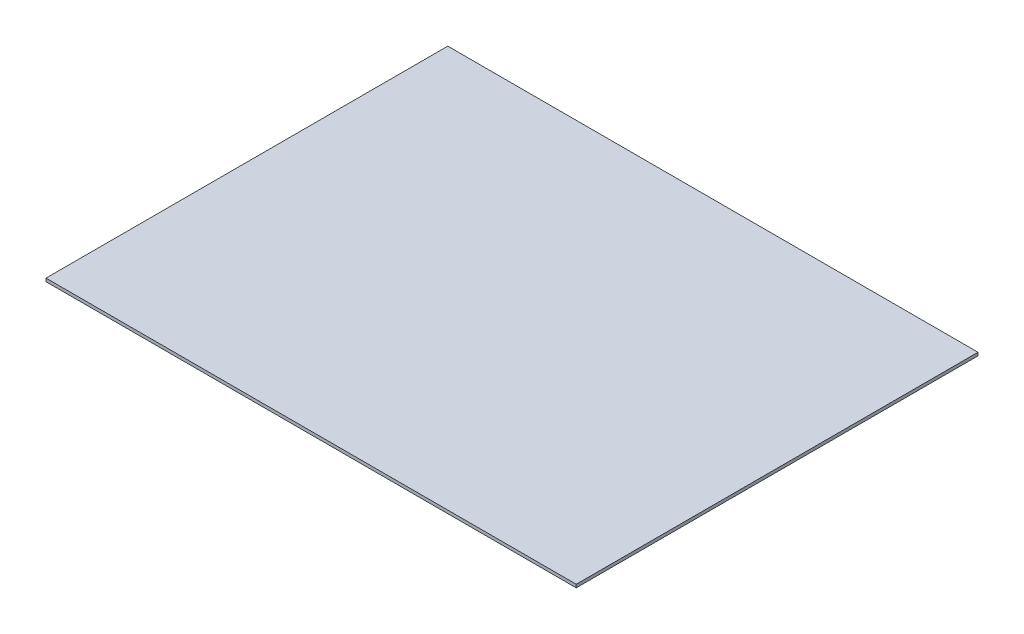
SolidWorks part; units mm, degrees
material "ABS"
ref_plane "Front Plane" through (0, 0, 0) normal (0, 0, 1) x (1, 0, 0)
ref_plane "Top Plane" through (0, 0, 0) normal (0, 1, 0) x (1, 0, 0)
ref_plane "Right Plane" through (0, 0, 0) normal (1, 0, 0) x (0, 0, -1)
sketch "Sketch1" plane through (0, 0, 0) normal (0, 1, 0) x (1, 0, 0)
  line L1 (-268.5, -203.454) -> (268.5, -203.454)
  line L2 (-268.5, -203.454) -> (-268.5, 203.454)
  line L3 (-268.5, 203.454) -> (268.5, 203.454)
  line L4 (268.5, -203.454) -> (268.5, 203.454)
  line L5 (-268.5, -203.454) -> (268.5, 203.454) construction
  line L6 (-268.5, 203.454) -> (268.5, -203.454) construction
  point P0 (0, 0)
  dimension "D1" = 537
  dimension "D2" = 406.908
extrude "Boss-Extrude1" add sketch "Sketch1" along normal blind 3.175
